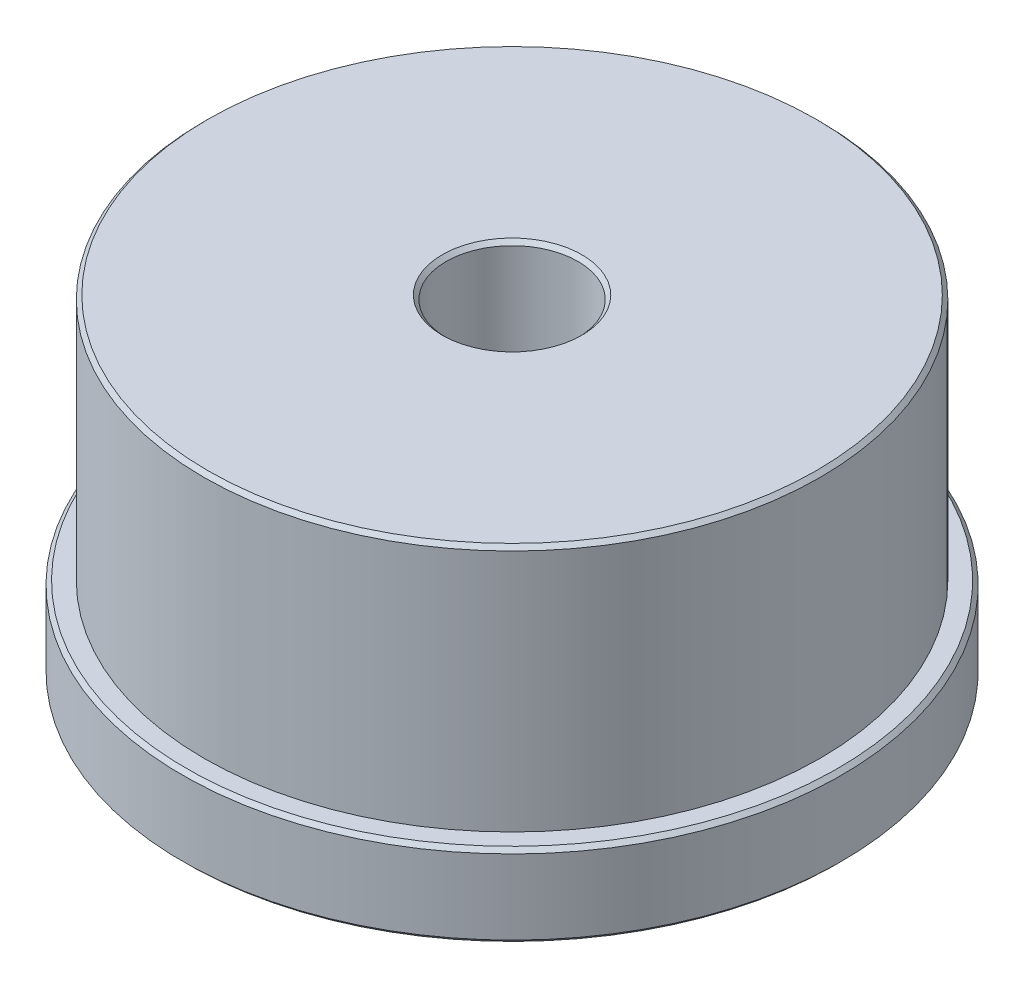
SolidWorks part; units mm, degrees
material "Nylon 101"
ref_plane "Front Plane" through (0, 0, 0) normal (0, 0, 1) x (1, 0, 0)
ref_plane "Top Plane" through (0, 0, 0) normal (0, 1, 0) x (1, 0, 0)
ref_plane "Right Plane" through (0, 0, 0) normal (1, 0, 0) x (0, 0, -1)
sketch "Sketch1" plane through (0, 0, 0) normal (0, 1, 0) x (1, 0, 0)
  circle A0 centre (0, 0) radius 23.749
  dimension "D1" = 47.498
extrude "Boss-Extrude1" add sketch "Sketch1" along normal blind 19.05
sketch "Sketch2" plane through (0, 0, 0) normal (0, -1, 0) x (1, 0, 0)
  circle A0 centre (0, 0) radius 25.4
  dimension "D1" = 50.8
extrude "Boss-Extrude2" add sketch "Sketch2" along normal blind 6.35
sketch "Sketch3" plane through (0, -6.35, 0) normal (0, -1, 0) x (1, 0, 0)
  circle A0 centre (0, 0) radius 5.08
  dimension "D1" = 10.16
extrude "Cut-Extrude1" cut sketch "Sketch3" against normal through all
sketch "Sketch4" plane through (0, -6.35, 0) normal (0, -1, 0) x (1, 0, 0)
  circle A0 centre (0, 0) radius 11.1125
  dimension "D1" = 22.225
extrude "Cut-Extrude2" cut sketch "Sketch4" against normal blind 5.5372
chamfer "Chamfer1" distance 0.3 angle 45 6 edges at (0, -0.8128, -5.08) (0, 0, -25.4) (0, -6.35, -25.4) (0, -6.35, -11.1125) (0, 19.05, 23.749) (0, 19.05, -5.08)
equation "\"D1@Chamfer1\"=.3mm"
